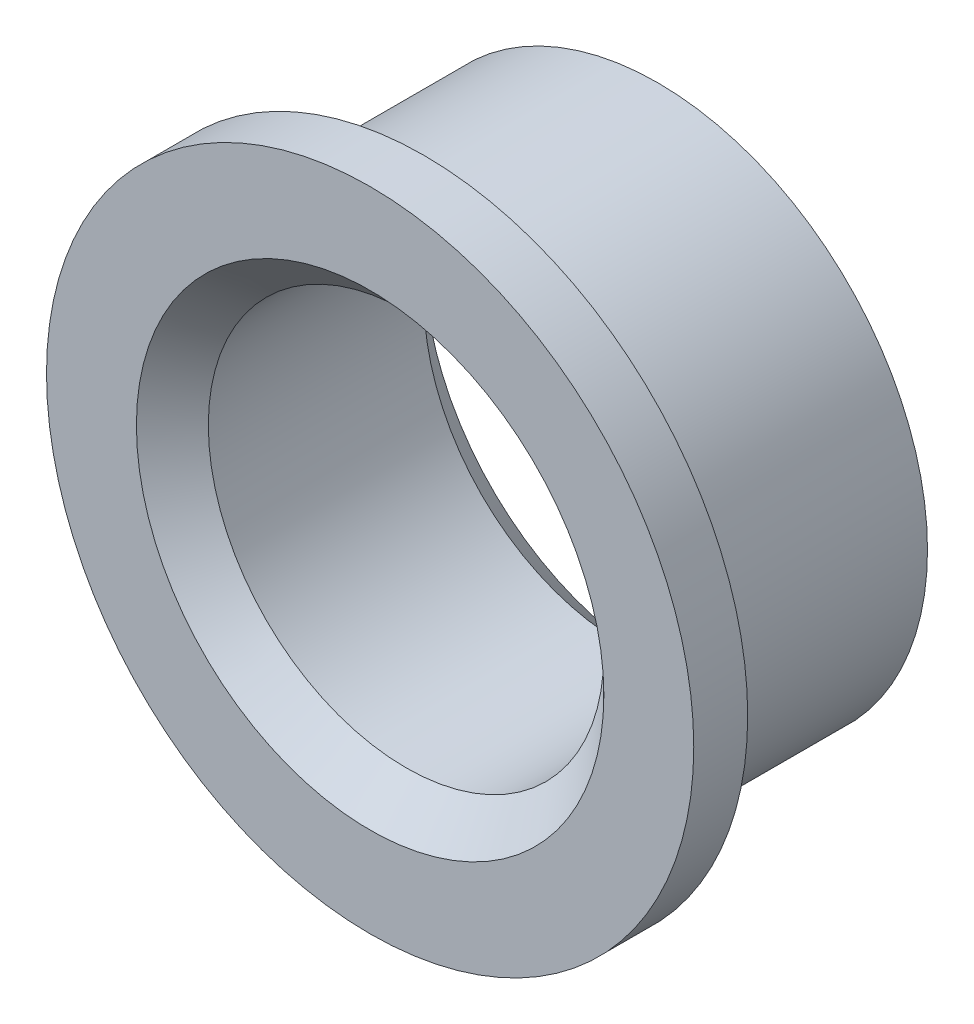
SolidWorks part; units mm, degrees
ref_plane "Front Plane" through (0, 0, 0) normal (0, 0, 1) x (1, 0, 0)
ref_plane "Top Plane" through (0, 0, 0) normal (0, 1, 0) x (1, 0, 0)
ref_plane "Right Plane" through (0, 0, 0) normal (1, 0, 0) x (0, 0, -1)
sketch "Sketch1" plane through (0, 0, 0) normal (1, 0, 0) x (0, 0, -1)
  line L0 (8, 5.5) -> (0, 5.5)
  line L1 (0, 5.5) -> (0, 9)
  line L2 (0, 9) -> (1.5, 9)
  line L3 (1.5, 9) -> (1.5, 7.5)
  line L4 (1.5, 7.5) -> (8, 7.5)
  line L5 (8, 7.5) -> (8, 5.5)
  line L6 (0, 0) -> (16.4878, 0) construction
  point P9 (0, 0)
  dimension "D1" = 8
  dimension "D2" = 5.5
  dimension "D3" = 7.5
  dimension "D4" = 9
  dimension "D5" = 1.5
revolve "Revolve1" add sketch "Sketch1" angle 360 about L6
chamfer "Chamfer1" distance 1 angle 45 2 edges at (5.5, 0, -8) (5.5, 0, 0)
